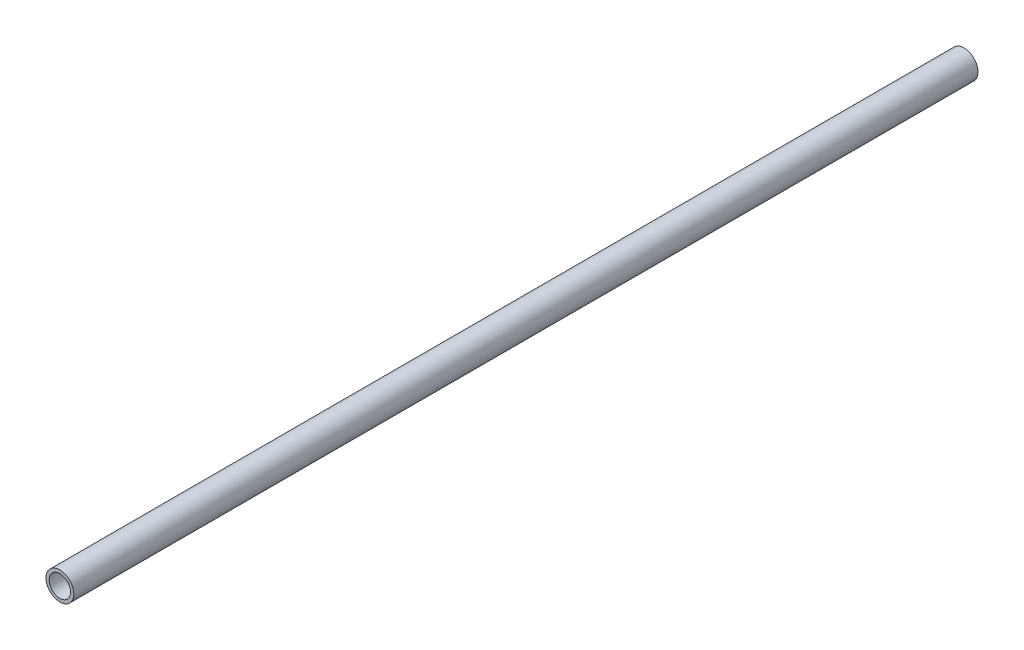
SolidWorks part; units mm, degrees
ref_plane "Front Plane" through (0, 0, 0) normal (0, 0, 1) x (1, 0, 0)
ref_plane "Top Plane" through (0, 0, 0) normal (0, 1, 0) x (1, 0, 0)
ref_plane "Right Plane" through (0, 0, 0) normal (1, 0, 0) x (0, 0, -1)
sketch "Sketch1" plane through (0, 0, 0) normal (0, 0, 1) x (1, 0, 0)
  line L0 (-6.35, 0) -> (6.35, 0) construction
  line L1 (0, -6.35) -> (0, 6.35) construction
  circle A0 centre (0, 0) radius 6.35
  circle A1 centre (0, 0) radius 4.8768
  point P4 (0, 0)
  point P9 (0, 0)
  point P10 (4.8768, 0)
  dimension "ID" = 9.7536
  dimension "OD" = 12.7
  dimension "Wall Thickness" = 1.4732
sketch "Sketch2" plane through (0, 0, 0) normal (1, 0, 0) x (0, 0, -1)
  line L0 (206.375, 6.35) -> (-206.375, 6.35) construction
  line L1 (0, 6.35) -> (0, -6.35) construction
  point P3 (-191.77, 6.35)
  point P4 (0, 6.35)
  point P5 (191.77, 6.35)
  dimension "Length" = 412.75
  dimension "D1" = 14.605
  dimension "D2" = 14.605
sketch "Sketch3" plane through (0, 0, 0) normal (0, 0, 1) x (1, 0, 0)
  line L0 (0, -6.35) -> (0, 6.35) construction
  circle A0 centre (0, 0) radius 6.35
  circle A1 centre (0, 0) radius 4.8768
  circle A2 centre (0, 0) radius 4.8768 construction
extrude "Boss-Extrude1" add sketch "Sketch3" along normal mid plane 412.75
equation "\"D1@Boss-Extrude1\" = \"Length@Sketch2\""
equation "\"D1@Sketch2\"=\"OD@Sketch1\"*1.15"
equation "\"D2@Sketch2\"=\"D1@Sketch2\""
